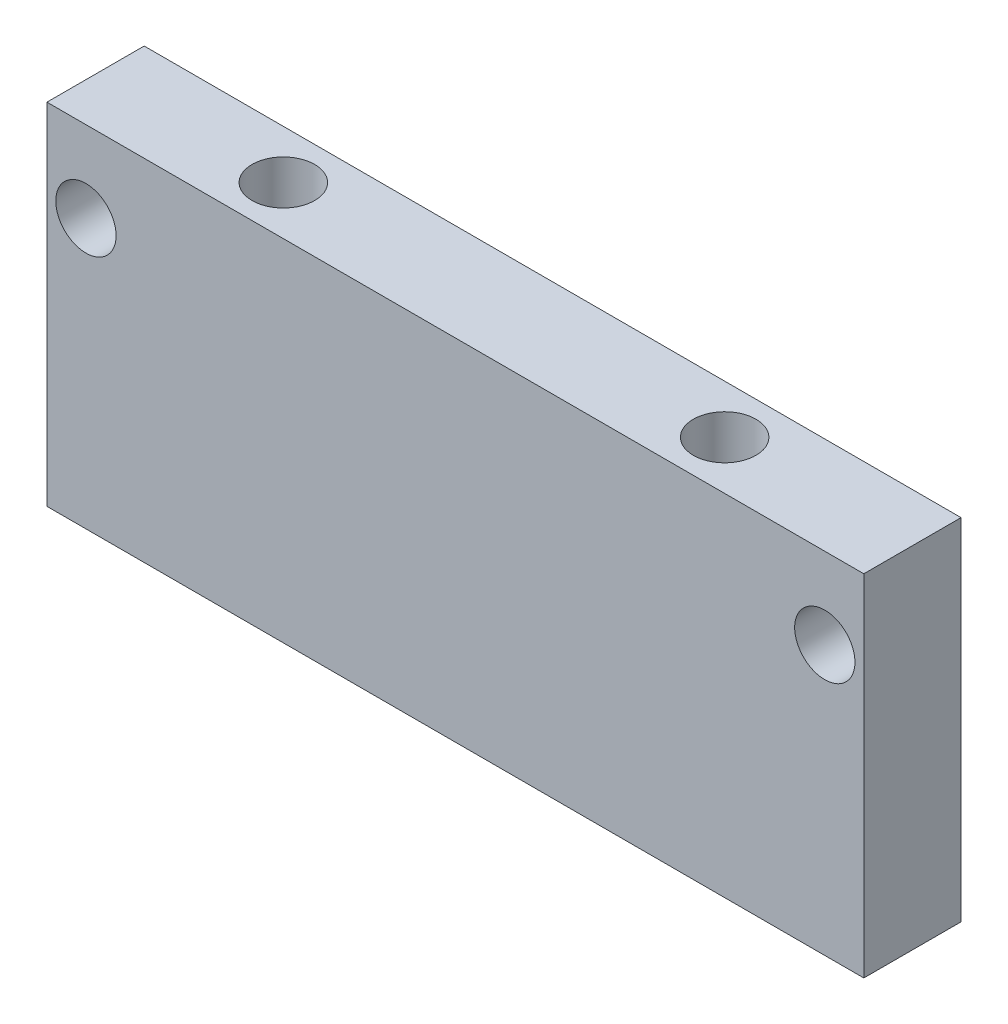
SolidWorks part; units mm, degrees
ref_plane "前视基准面" through (0, 0, 0) normal (0, 0, 1) x (1, 0, 0)
ref_plane "上视基准面" through (0, 0, 0) normal (0, 1, 0) x (1, 0, 0)
ref_plane "右视基准面" through (0, 0, 0) normal (1, 0, 0) x (0, 0, -1)
other "Configuration Table"
sketch "草图1" plane through (0, 0, 0) normal (0, 1, 0) x (1, 0, 0)
  line L1 (-21, 2.5) -> (21, 2.5)
  line L2 (-21, 2.5) -> (-21, -2.5)
  line L3 (-21, -2.5) -> (21, -2.5)
  line L4 (21, 2.5) -> (21, -2.5)
  line L5 (-21, 2.5) -> (21, -2.5) construction
  line L6 (-21, -2.5) -> (21, 2.5) construction
  point P0 (0, 0)
  dimension "D1" = 42
  dimension "D2" = 5
extrude "凸台-拉伸1" add sketch "草图1" along normal blind 18
sketch "草图2" plane through (0, 0, 2.5) normal (0, 0, 1) x (1, 0, 0)
  line L0 (-18.995, 13.83) -> (18.995, 13.83) construction
  line L1 (0, 0) -> (0, 13.83) construction
  line L2 (-21, 0) -> (21, 0) construction
  circle A0 centre (-18.995, 13.83) radius 1.55
  circle A1 centre (18.995, 13.83) radius 1.55
  point P8 (0, 0)
  point P9 (-18.995, 14.5655)
  point P10 (23.477, 9.7829)
  point P13 (3.4131, 7.0192)
  dimension "D1" = 18.995
  dimension "D3" = 3.1
  dimension "D4" = 3.1
  dimension "D2" = 18.995
  dimension "D5" = 13.83
extrude "切除-拉伸1" cut sketch "草图2" against normal blind 14.93
sketch "草图3" plane through (0, 18, 0) normal (0, 1, 0) x (1, 0, 0)
  circle A0 centre (-11.345, 0) radius 1.61
  circle A1 centre (11.345, 0) radius 1.61
  dimension "D1" = 3.22
  dimension "D2" = 3.22
  dimension "D3" = 11.345
  dimension "D4" = 11.345
extrude "切除-拉伸2" cut sketch "草图3" against normal through all
